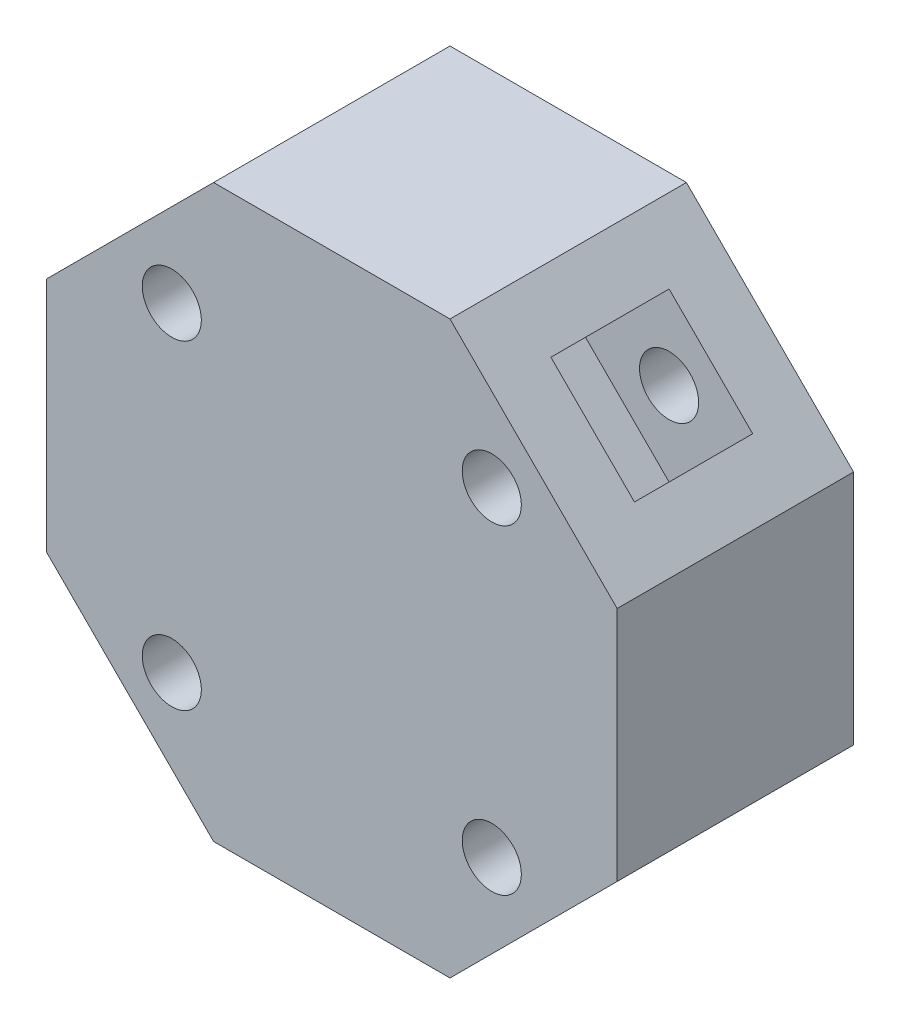
SolidWorks part; units mm, degrees
ref_plane "Front Plane" through (0, 0, 0) normal (0, 0, 1) x (1, 0, 0)
ref_plane "Top Plane" through (0, 0, 0) normal (0, 1, 0) x (1, 0, 0)
ref_plane "Right Plane" through (0, 0, 0) normal (1, 0, 0) x (0, 0, -1)
sketch "Sketch1" plane through (0, 0, 0) normal (0, 0, 1) x (1, 0, 0)
  line L0 (-30.6605, 12.7) -> (-30.6605, -12.7)
  line L1 (-12.7, -30.6605) -> (12.7, -30.6605)
  line L2 (12.7, -30.6605) -> (30.6605, -12.7)
  line L3 (30.6605, -12.7) -> (30.6605, 12.7)
  line L4 (30.6605, 12.7) -> (12.7, 30.6605)
  line L5 (12.7, 30.6605) -> (-12.7, 30.6605)
  line L6 (-12.7, 30.6605) -> (-30.6605, 12.7)
  line L7 (-30.6605, -12.7) -> (-12.7, -30.6605)
  line L8 (0, 0) -> (0, 37.9758) construction
  circle A0 centre (0, 0) radius 30.6605 construction
  dimension "D1" = 25.4
  dimension "D2" = 12.7
extrude "Boss-Extrude1" add sketch "Sketch1" along normal blind 25.4
sketch "Sketch2" plane through (21.6803, 21.6803, 0) normal (0.7071, 0.7071, 0) x (0, 0, -1)
  line L0 (-25.4, 0) -> (0, 0) construction
  line L1 (-25.4, -12.7) -> (-25.4, 12.7) construction
  line L2 (-12.7, 0) -> (-12.7, 12.7) construction
  line L3 (-25.4, 12.7) -> (0, 12.7) construction
  line L5 (-6.35, -6.35) -> (-19.05, -6.35)
  line L6 (-6.35, -6.35) -> (-6.35, 6.35)
  line L7 (-6.35, 6.35) -> (-19.05, 6.35)
  line L8 (-19.05, -6.35) -> (-19.05, 6.35)
  line L9 (-6.35, -6.35) -> (-19.05, 6.35) construction
  line L10 (-6.35, 6.35) -> (-19.05, -6.35) construction
  dimension "D1" = 12.7
  dimension "D2" = 12.7
extrude "Cut-Extrude1" cut sketch "Sketch2" against normal blind 12.7
ref_plane "Plane1" through (0, 0, 0) normal (1, 0, 0) x (0, 0, -1)
mirror "Mirror1" about plane through (0, 0, 0) normal (1, 0, 0) of "Cut-Extrude1"
ref_plane "Plane2" through (0, 0, 0) normal (0, 1, 0) x (1, 0, 0)
mirror "Mirror2" about plane through (0, 0, 0) normal (0, 1, 0) of "Mirror1", "Cut-Extrude1"
sketch "Sketch3" plane through (0, 0, 25.4) normal (0, 0, 1) x (1, 0, 0)
  line L0 (-21.6803, 21.6803) -> (-17.1901, 17.1901) construction
  line L1 (-12.7, 30.6605) -> (-30.6605, 12.7) construction
  line L2 (0, 30.6605) -> (0, -30.6605) construction
  line L3 (12.7, 30.6605) -> (-12.7, 30.6605) construction
  line L4 (-12.7, -30.6605) -> (12.7, -30.6605) construction
  line L5 (-30.6605, 0) -> (30.6605, 0) construction
  line L6 (-30.6605, 12.7) -> (-30.6605, -12.7) construction
  line L7 (30.6605, -12.7) -> (30.6605, 12.7) construction
  circle A0 centre (-17.1901, 17.1901) radius 3.175
  circle A1 centre (-17.1901, -17.1901) radius 3.175
  circle A2 centre (17.1901, -17.1901) radius 3.175
  circle A3 centre (17.1901, 17.1901) radius 3.175
  dimension "D1" = 6.35
  dimension "D3" = 90
  dimension "D2" = 6.35
extrude "Cut-Extrude2" cut sketch "Sketch3" against normal through all
